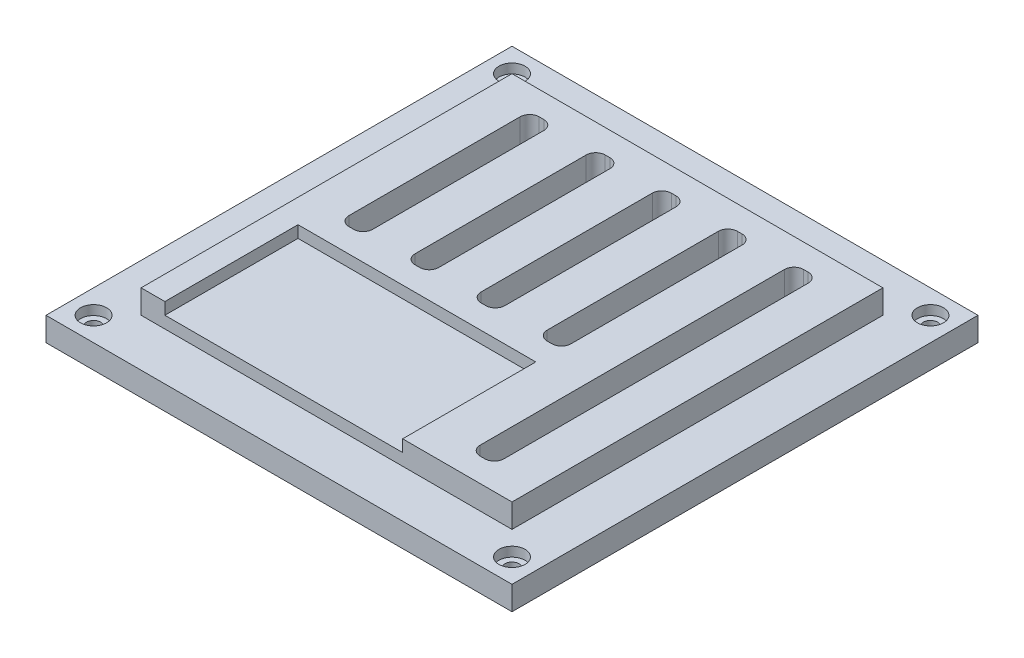
SolidWorks part; units mm, degrees
ref_plane "Front Plane" through (0, 0, 0) normal (0, 0, 1) x (1, 0, 0)
ref_plane "Top Plane" through (0, 0, 0) normal (0, 1, 0) x (1, 0, 0)
ref_plane "Right Plane" through (0, 0, 0) normal (1, 0, 0) x (0, 0, -1)
sketch "Sketch1" plane through (0, 0, 0) normal (0, 1, 0) x (1, 0, 0)
  line L1 (-49, 49) -> (49, 49)
  line L2 (-49, 49) -> (-49, -49)
  line L3 (-49, -49) -> (49, -49)
  line L4 (49, 49) -> (49, -49)
  point P0 (0, 0)
extrude "Boss-Extrude2" add sketch "Sketch1" along normal blind 10
sketch "Sketch2" plane through (0, 10, 0) normal (0, 1, 0) x (1, 0, 0)
  line L1 (-39, 39) -> (39, 39)
  line L2 (-39, 39) -> (-39, -39)
  line L3 (-39, -39) -> (39, -39)
  line L4 (39, 39) -> (39, -39)
  line L5 (49, -49) -> (-49, -49)
  line L6 (49, -49) -> (49, 49)
  line L7 (49, 49) -> (-49, 49)
  line L8 (-49, -49) -> (-49, 49)
  point P0 (0, 0)
  point P6 (0, 0)
extrude "Cut-Extrude2" cut sketch "Sketch2" against normal blind 5
sketch "Sketch3" plane through (0, 5, 0) normal (0, 1, 0) x (1, 0, 0)
  line L0 (0, 44) -> (0, 40.3919)
  line L1 (44, -44) -> (-44, -44) construction
  line L2 (44, -44) -> (44, 44) construction
  line L3 (44, 44) -> (-44, 44) construction
  line L4 (-44, -44) -> (-44, 44) construction
  line L5 (-44, 0) -> (-40.9956, 0)
  circle A0 centre (-44, 44) radius 2.75
  circle A1 centre (44, 44) radius 2.75
  circle A2 centre (44, -44) radius 2.75
  circle A3 centre (-44, -44) radius 2.75
  point P0 (0, 0)
  dimension "D3" = 5.5
  dimension "D1" = 88
  dimension "D2" = 88
extrude "Cut-Extrude3" cut sketch "Sketch3" against normal blind 2 contours A3 | A2 | A0 | A1
sketch "Sketch4" plane through (0, 3, 0) normal (0, 1, 0) x (1, 0, 0)
  line L1 (-42.5, 44) -> (42.5, 44) construction
  line L2 (-44, 42.5) -> (-44, -42.5) construction
  line L3 (-42.5, -44) -> (42.5, -44) construction
  line L4 (44, 42.5) -> (44, -42.5) construction
  circle A0 centre (-44, 44) radius 1.5
  circle A1 centre (44, 44) radius 1.5
  circle A2 centre (44, -44) radius 1.5
  circle A3 centre (-44, -44) radius 1.5
extrude "Cut-Extrude4" cut sketch "Sketch4" against normal blind 9
sketch "Sketch6" plane through (0, 10, 0) normal (0, 1, 0) x (1, 0, 0)
  line L1 (-39, -39) -> (39, -39) construction
  line L6 (-34, -39) -> (-34, -11)
  line L7 (-34, -11) -> (16, -11)
  line L8 (16, -11) -> (16, -39)
  line L9 (-39, -39) -> (39, -39) construction
  line L10 (16, -39) -> (-34, -39)
extrude "Cut-Extrude6" cut sketch "Sketch6" against normal blind 2.5
sketch "Sketch7" plane through (0, 10, 0) normal (0, 1, 0) x (1, 0, 0)
  line L0 (0, 39) -> (0, 34)
  line L1 (39, 39) -> (-39, 39) construction
  line L2 (-9, -11) -> (-9, -6)
  line L3 (16, -11) -> (-34, -11) construction
  line L4 (-39.514, 34) -> (-34.514, 34)
  line L5 (11.4, 32) -> (11.4, -4)
  line L6 (-28.3, -6) -> (-27.3, -6)
  line L7 (-16.4, 32) -> (-16.4, -4)
  line L8 (27.3, -34) -> (28.3, -34)
  line L11 (13.4, 34) -> (14.4, 34)
  line L12 (16.4, 32) -> (16.4, -4)
  line L13 (13.4, -6) -> (14.4, -6)
  line L14 (-34.514, -6) -> (-29.4913, -6)
  line L18 (-34.514, -6) -> (-29.4913, -6)
  line L22 (-0.5, -6) -> (0.5, -6)
  line L23 (-0.5, 34) -> (0.5, 34)
  line L24 (-2.5, 32) -> (-2.5, -4)
  line L25 (-2.5, -6) -> (2.5, -6)
  line L26 (2.5, 32) -> (2.5, -4)
  line L27 (25.3, 32) -> (25.3, -6)
  line L28 (27.3, 34) -> (28.3, 34)
  line L29 (-2.5, 34) -> (2.5, 34)
  line L30 (30.3, 32) -> (30.3, -6)
  line L32 (25.3, -6) -> (25.3, -32)
  line L33 (30.3, -6) -> (30.3, -32)
  line L34 (-14.4, 34) -> (-13.4, 34)
  line L35 (25.3, -6) -> (30.3, -6) [skipped]
  line L36 (-11.4, 32) -> (-11.4, -4)
  line L37 (-14.4, -6) -> (-13.4, -6)
  line L38 (-30.3, 32) -> (-30.3, -4)
  line L39 (-28.3, 34) -> (-27.3, 34)
  line L40 (-25.3, 32) -> (-25.3, -4)
  line L41 (-30.3, -6) -> (-25.3, -6)
  arc A0 (28.3, 34) -> (30.3, 32) centre (28.3, 32) cw
  arc A1 (25.3, 32) -> (27.3, 34) centre (27.3, 32) cw
  arc A2 (16.4, 32) -> (14.4, 34) centre (14.4, 32) ccw
  arc A3 (11.4, 32) -> (13.4, 34) centre (13.4, 32) cw
  arc A4 (0.5, 34) -> (2.5, 32) centre (0.5, 32) cw
  arc A5 (-2.5, 32) -> (-0.5, 34) centre (-0.5, 32) cw
  arc A6 (-11.4, 32) -> (-13.4, 34) centre (-13.4, 32) ccw
  arc A7 (-16.4, 32) -> (-14.4, 34) centre (-14.4, 32) cw
  arc A8 (-27.3, -6) -> (-25.3, -4) centre (-27.3, -4) ccw
  arc A9 (-28.3, -6) -> (-30.3, -4) centre (-28.3, -4) cw
  arc A10 (-25.3, 32) -> (-27.3, 34) centre (-27.3, 32) ccw
  arc A11 (-30.3, 32) -> (-28.3, 34) centre (-28.3, 32) cw
  arc A12 (28.3, -34) -> (30.3, -32) centre (28.3, -32) ccw
  arc A13 (27.3, -34) -> (25.3, -32) centre (27.3, -32) cw
  arc A14 (14.4, -6) -> (16.4, -4) centre (14.4, -4) ccw
  arc A15 (13.4, -6) -> (11.4, -4) centre (13.4, -4) cw
  arc A16 (0.5, -6) -> (2.5, -4) centre (0.5, -4) ccw
  arc A17 (-0.5, -6) -> (-2.5, -4) centre (-0.5, -4) cw
  arc A18 (-13.4, -6) -> (-11.4, -4) centre (-13.4, -4) ccw
  arc A19 (-14.4, -6) -> (-16.4, -4) centre (-14.4, -4) cw
  point P14 (0, 34)
  point P17 (-9, -6)
  point P34 (0, 14)
  dimension "D3" = 2
  dimension "D4" = 2
  dimension "D1" = 3
  dimension "D2" = 3
extrude "Cut-Extrude8" cut sketch "Sketch7" against normal blind 11.5 contours A11 L38 A9 L6 A8 L40 A10 L39 | A19 L37 A18 L36 A6 L34 A7 L7 | A17 L22 A16 L26 A4 L23 A5 L24 | A15 L13 A14 L12 A2 L11 A3 L5 | A13 L8 A12 L33 L30 A0 L28 A1 L27 L32
